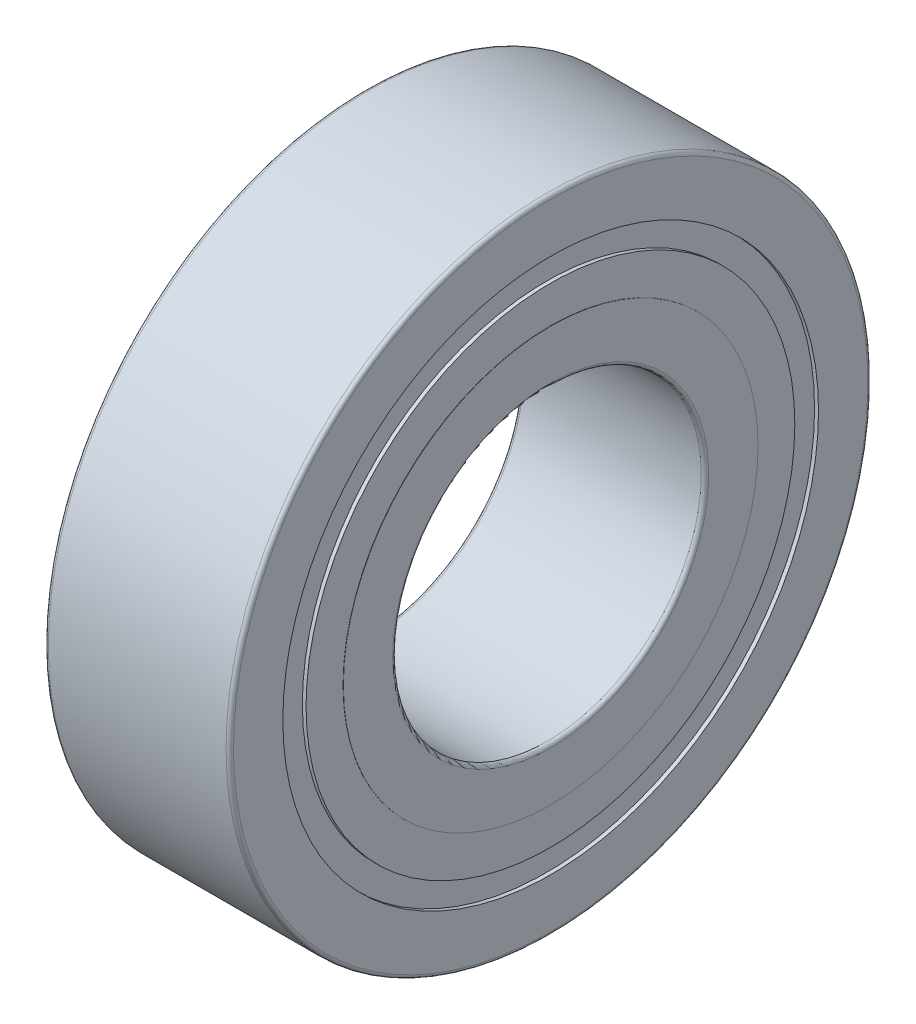
SolidWorks part; units mm, degrees
material "Low Carbon Steel"
ref_plane "Front Plane" through (0, 0, 0) normal (0, 0, 1) x (1, 0, 0)
ref_plane "Top Plane" through (0, 0, 0) normal (0, 1, 0) x (1, 0, 0)
ref_plane "Right Plane" through (0, 0, 0) normal (1, 0, 0) x (0, 0, -1)
ref_plane "Plane1" through (0, 0, 0) normal (0, 0, 1) x (1, 0, 0)
sketch "Sketch1" plane through (0, 0, 0) normal (0, 0, 1) x (1, 0, 0)
  line L0 (-7.2, 12.5) -> (7.2, 12.5)
  line L1 (7.5, 12.8) -> (7.5, 25.7)
  line L2 (7.2, 26) -> (-7.2, 26)
  line L3 (-7.5, 25.7) -> (-7.5, 12.8)
  line L4 (50, 0) -> (-50, 0) construction
  arc A0 (-7.5, 12.8) -> (-7.2, 12.5) centre (-7.2, 12.8) ccw
  arc A1 (7.2, 12.5) -> (7.5, 12.8) centre (7.2, 12.8) ccw
  arc A2 (7.5, 25.7) -> (7.2, 26) centre (7.2, 25.7) ccw
  arc A3 (-7.2, 26) -> (-7.5, 25.7) centre (-7.2, 25.7) ccw
revolve "Revolve1" add sketch "Sketch1" angle 360 about L4
ref_plane "Plane2" through (0, 0, 0) normal (0, 0, 1) x (1, 0, 0)
sketch "Sketch2" plane through (0, 0, 0) normal (0, 0, 1) x (1, 0, 0)
  line L0 (-9.18, 21.7) -> (-9.18, 12.5)
  line L1 (-9.18, 12.5) -> (-7.5, 12.5)
  line L2 (-7.5, 12.5) -> (-7.5, 16.8)
  line L3 (-7.5, 16.8) -> (-7.48, 16.8)
  line L4 (-7.48, 16.8) -> (-7.48, 19.8)
  line L5 (-7.48, 19.8) -> (-7.18, 19.8)
  line L6 (-7.18, 19.8) -> (-7.18, 21.7)
  line L7 (-7.18, 21.7) -> (-9.18, 21.7)
  line L8 (50, 0) -> (-50, 0) construction
revolve "Cut-Revolve1" cut sketch "Sketch2" angle 360 about L8
ref_plane "Plane3" through (0, 0, 0) normal (0, 0, 1) x (1, 0, 0)
sketch "Sketch3" plane through (0, 0, 0) normal (0, 0, 1) x (1, 0, 0)
  line L0 (7.18, 19.8) -> (7.48, 19.8)
  line L1 (7.48, 19.8) -> (7.48, 16.8)
  line L2 (7.48, 16.8) -> (7.5, 16.8)
  line L3 (7.5, 16.8) -> (7.5, 12.5)
  line L4 (7.5, 12.5) -> (9.18, 12.5)
  line L5 (9.18, 12.5) -> (9.18, 21.7)
  line L6 (9.18, 21.7) -> (7.18, 21.7)
  line L7 (7.18, 21.7) -> (7.18, 19.8)
  line L8 (50, 0) -> (-50, 0) construction
revolve "Cut-Revolve2" cut sketch "Sketch3" angle 360 about L8
other "Freeze***"
